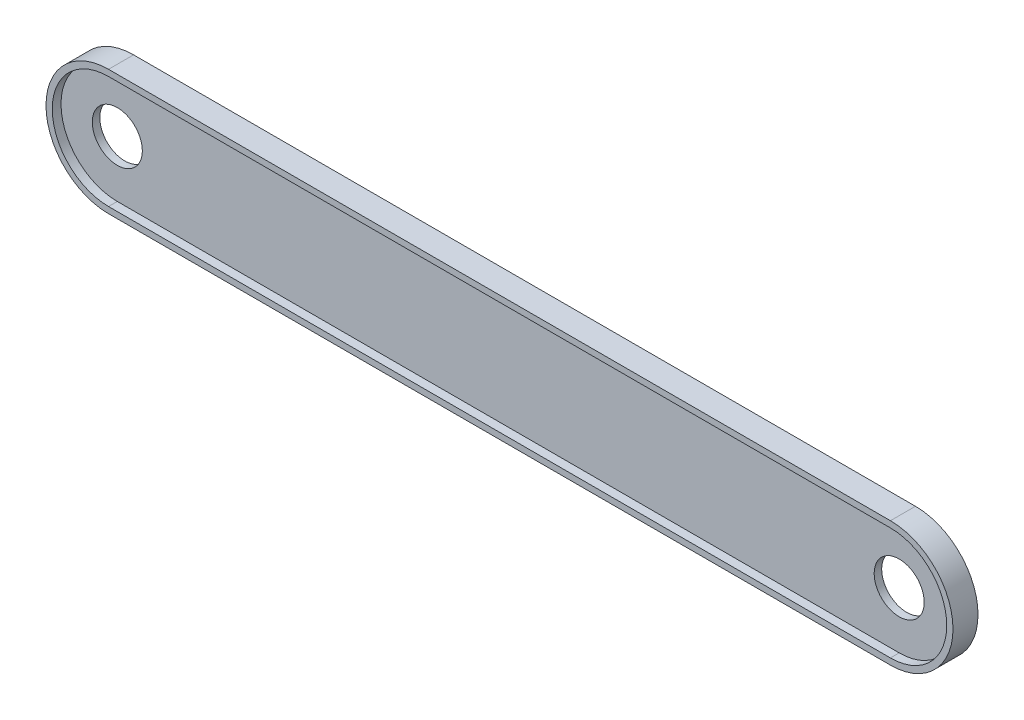
SolidWorks part; units mm, degrees
ref_plane "Front Plane" through (0, 0, 0) normal (0, 0, 1) x (1, 0, 0)
ref_plane "Top Plane" through (0, 0, 0) normal (0, 1, 0) x (1, 0, 0)
ref_plane "Right Plane" through (0, 0, 0) normal (1, 0, 0) x (0, 0, -1)
sketch "Sketch1" plane through (0, 0, 0) normal (0, 0, 1) x (1, 0, 0)
  line L0 (-397.3593, 0) -> (412.9422, 0) construction
  line L1 (0, 304.6482) -> (0, -306.2186) construction
  line L2 (-312.5, 0) -> (312.5, 0) construction
  line L3 (-312.5, 50) -> (312.5, 50)
  line L4 (-312.5, -50) -> (312.5, -50)
  line L5 (-312.5, 55) -> (312.5, 55)
  line L6 (-312.5, -55) -> (312.5, -55)
  arc A0 (-312.5, 50) -> (-312.5, -50) centre (-312.5, 0) ccw
  arc A1 (312.5, -50) -> (312.5, 50) centre (312.5, 0) ccw
  circle A2 centre (312.5, 0) radius 20
  circle A3 centre (-312.5, 0) radius 20
  arc A4 (312.5, -55) -> (312.5, 55) centre (312.5, 0) ccw
  arc A5 (-312.5, 55) -> (-312.5, -55) centre (-312.5, 0) ccw
  point P5 (0, 0)
  point P26 (0, 0)
  dimension "D4" = 5
  dimension "40" = 40
  dimension "D1" = 625
  dimension "D2" = 312.5
  dimension "D3" = 100
extrude "Boss-Extrude1" add sketch "Sketch1" along normal mid plane 20 contours L4 A1 L3 A0 A2 A3
sketch "Sketch2" plane through (0, 0, -10) normal (0, 0, -1) x (-1, 0, 0)
  line L0 (312.5, 45) -> (-312.5, 45)
  line L1 (312.5, -50) -> (-312.5, -50) construction
  line L2 (312.5, 50) -> (-312.5, 50) construction
  line L3 (312.5, -50) -> (-312.5, -50)
  line L4 (312.5, 50) -> (-312.5, 50)
  line L5 (312.5, -45) -> (-312.5, -45)
  circle A0 centre (-312.5, 0) radius 30
  circle A1 centre (312.5, 0) radius 30
  circle A2 centre (312.5, 0) radius 20 construction
  arc A3 (-312.5, 45) -> (-312.5, -45) centre (-312.5, 0) ccw
  circle A4 centre (-312.5, 0) radius 20 construction
  arc A5 (-312.5, 50) -> (-312.5, -50) centre (-312.5, 0) ccw construction
  arc A6 (312.5, -50) -> (312.5, 50) centre (312.5, 0) ccw construction
  arc A7 (-312.5, 50) -> (-312.5, -50) centre (-312.5, 0) ccw
  arc A8 (312.5, -50) -> (312.5, 50) centre (312.5, 0) ccw
  arc A9 (312.5, -45) -> (312.5, 45) centre (312.5, 0) ccw
  dimension "D1" = 10
  dimension "D2" = 10
  dimension "D3" = 5
extrude "Cut-Extrude1" cut sketch "Sketch2" against normal blind 7 contours L0 A3 L5 A9
ref_plane "Plane1" through (0, 0, 0) normal (0, 0, 1) x (1, 0, 0)
mirror "Mirror2" about plane through (0, 0, 0) normal (0, 0, 1) of "Cut-Extrude1"
